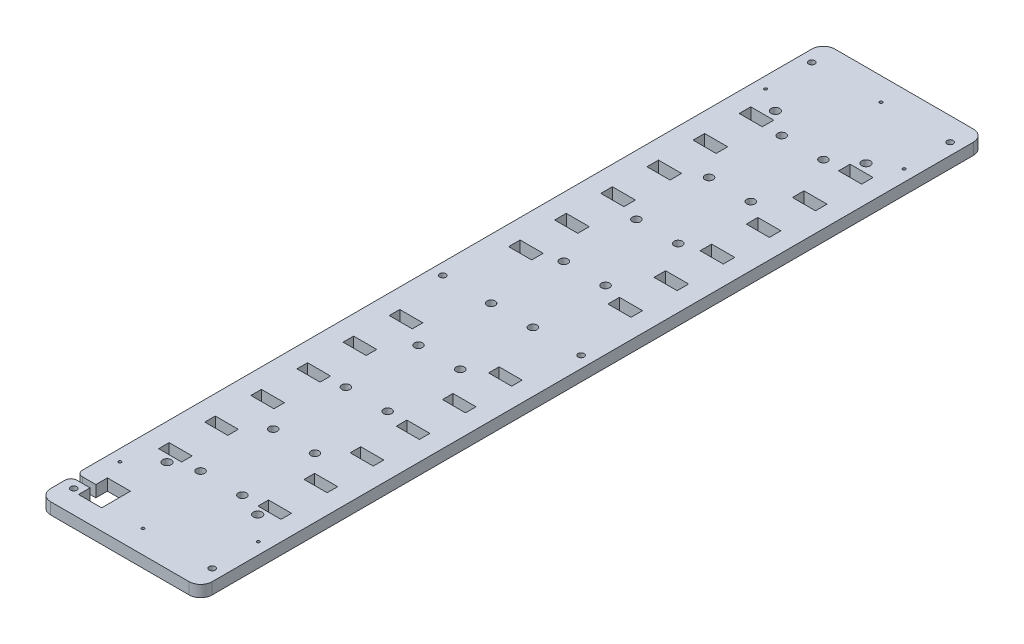
SolidWorks part; units mm, degrees
material "Acrylic (Medium-high impact)"
ref_plane "Front Plane" through (0, 0, 0) normal (0, 0, 1) x (1, 0, 0)
ref_plane "Top Plane" through (0, 0, 0) normal (0, 1, 0) x (1, 0, 0)
ref_plane "Right Plane" through (0, 0, 0) normal (1, 0, 0) x (0, 0, -1)
sketch "Sketch1" plane through (0, 0, 0) normal (0, 1, 0) x (1, 0, 0)
  line L1 (0, 0) -> (-88.9, 0)
  line L2 (0, 0) -> (0, -431.8)
  line L3 (0, -431.8) -> (-88.9, -431.8)
  line L4 (-88.9, 0) -> (-88.9, -431.8)
  dimension "D1" = 88.9
  dimension "D2" = 431.8
extrude "Boss-Extrude1" add sketch "Sketch1" along normal blind 6.35
hole_wizard "M4 Clearance Hole2" positions "Sketch9" profile "Sketch8" hole size "M4" standard "Ansi Metric"
sketch "Sketch9" plane through (0, 6.35, 0) normal (0, 1, 0) x (-1, 0, 0)
  line L2 (0, 215.9) -> (88.9, 215.9) construction
  line L3 (0, 431.8) -> (0, 0) construction
  line L4 (88.9, 0) -> (88.9, 431.8) construction
  line L6 (44.45, 431.8) -> (44.45, 0) construction
  line L7 (88.9, 431.8) -> (0, 431.8) construction
  line L8 (0, 0) -> (88.9, 0) construction
  line L10 (32.95, 215.9) -> (44.45, 215.9) construction
  line L11 (44.45, 215.9) -> (55.95, 215.9) construction
  line L14 (32.95, 375.9) -> (44.45, 375.9) construction
  line L15 (44.45, 375.9) -> (55.95, 375.9) construction
  line L17 (55.95, 55.9) -> (44.45, 55.9) construction
  line L18 (44.45, 55.9) -> (32.95, 55.9) construction
  point P0 (32.95, 215.9)
  point P1 (55.95, 215.9)
  point P76 (32.95, 255.9)
  point P77 (55.95, 255.9)
  point P78 (32.95, 295.9)
  point P79 (55.95, 295.9)
  point P80 (32.95, 335.9)
  point P81 (55.95, 335.9)
  point P82 (32.95, 375.9)
  point P83 (55.95, 375.9)
  point P95 (32.95, 175.9)
  point P96 (55.95, 175.9)
  point P97 (32.95, 135.9)
  point P98 (55.95, 135.9)
  point P99 (32.95, 95.9)
  point P100 (55.95, 95.9)
  point P101 (32.95, 55.9)
  point P102 (55.95, 55.9)
  dimension "D1" = 23
  dimension "D4" = 5
  dimension "D5" = 40
  dimension "D3" = 40
  dimension "D2" = 5
sketch "Sketch8" plane through (-32.95, 6.35, 215.9) normal (1, 0, 0) x (0, 0, 1)
  line L0 (0, 0) -> (0, 14.0519)
  line L1 (0, 14.0519) -> (2.25, 12.7)
  line L2 (2.25, 12.7) -> (2.25, 0)
  line L5 (2.25, 0) -> (0, 0)
  line L10 (0, 14.0519) -> (-2.25, 12.7) construction
  line L11 (0, -6.35) -> (0, 107.95) construction
  dimension "Hole Dia." = 4.5
  dimension "Hole Depth" = 12.7
  dimension "Drill Angle" = 118
hole_wizard "M3 Clearance Hole1" positions "Sketch4" profile "Sketch3" hole size "M3" standard "Ansi Metric"
sketch "Sketch4" plane through (0, 6.35, 0) normal (0, 1, 0) x (-1, 0, 0)
  line L0 (88.9, 12.7) -> (0, 12.7) construction
  line L1 (88.9, 0) -> (88.9, 431.8) construction
  line L2 (0, 431.8) -> (0, 0) construction
  line L4 (0, 0) -> (88.9, 0) construction
  line L5 (82.55, 0) -> (82.55, 431.8) construction
  line L6 (88.9, 431.8) -> (0, 431.8) construction
  line L8 (44.45, 0) -> (44.45, 431.8) construction
  line L10 (88.9, 215.9) -> (0, 215.9) construction
  line L12 (6.35, 12.7) -> (6.35, 431.8) construction
  point P0 (82.55, 12.7)
  point P27 (6.35, 12.7)
  point P28 (6.35, 419.1)
  point P29 (82.55, 419.1)
  point P30 (82.55, 215.9)
  point P32 (6.35, 215.9)
  dimension "D1" = 76.2
  dimension "D2" = 12.7
sketch "Sketch3" plane through (-82.55, 6.35, 12.7) normal (1, 0, 0) x (0, 0, 1)
  line L0 (0, 0) -> (0, 11.0215)
  line L1 (0, 11.0215) -> (1.7, 10)
  line L2 (1.7, 10) -> (1.7, 0)
  line L5 (1.7, 0) -> (0, 0)
  line L10 (0, 11.0215) -> (-1.7, 10) construction
  line L11 (0, -6.35) -> (0, 107.95) construction
  dimension "Hole Dia." = 3.4
  dimension "Hole Depth" = 10
  dimension "Drill Angle" = 118
sketch "Sketch5" plane through (0, 6.35, 0) normal (0, 1, 0) x (1, 0, 0)
  line L0 (-82.55, -12.7) -> (-6.35, -12.7) construction
  line L1 (-82.55, -12.7) -> (-82.55, -38.1) construction
  line L2 (-82.55, -38.1) -> (-6.35, -38.1) construction
  line L3 (-6.35, -38.1) -> (-6.35, -12.7) construction
  line L4 (-82.55, -215.9) -> (-6.35, -215.9) construction
  circle A0 centre (-44.45, -12.7) radius 0.7937
  circle A1 centre (-82.55, -38.1) radius 0.7937
  circle A2 centre (-6.35, -38.1) radius 0.7938
  circle A3 centre (-6.35, -393.7) radius 0.7938
  circle A4 centre (-82.55, -393.7) radius 0.7937
  circle A5 centre (-44.45, -419.1) radius 0.7938
  dimension "D1" = 1.5875
  dimension "D2" = 25.4
extrude "Cut-Extrude2" cut sketch "Sketch5" against normal through all
sketch "Sketch6" plane through (0, 6.35, 0) normal (0, 1, 0) x (-1, 0, 0)
  line L0 (44.45, 55.9) -> (44.45, 53.9) construction
  line L1 (78.15, 50.725) -> (65.45, 50.725)
  line L2 (78.15, 50.725) -> (78.15, 57.075)
  line L3 (78.15, 57.075) -> (65.45, 57.075)
  line L4 (65.45, 50.725) -> (65.45, 57.075)
  line L5 (65.45, 53.9) -> (23.45, 53.9) construction
  line L6 (32.95, 375.9) -> (55.95, 375.9) construction
  line L7 (23.45, 50.725) -> (23.45, 57.075)
  line L8 (10.75, 57.075) -> (23.45, 57.075)
  line L9 (10.75, 50.725) -> (10.75, 57.075)
  line L10 (10.75, 50.725) -> (23.45, 50.725)
  line L11 (78.15, 371) -> (65.45, 371)
  line L12 (78.15, 371) -> (78.15, 376.8)
  line L13 (78.15, 376.8) -> (65.45, 376.8)
  line L14 (65.45, 371) -> (65.45, 376.8)
  line L15 (23.45, 371) -> (23.45, 376.8)
  line L16 (10.75, 376.8) -> (23.45, 376.8)
  line L17 (10.75, 371) -> (10.75, 376.8)
  line L18 (10.75, 371) -> (23.45, 371)
  line L19 (65.45, 373.9) -> (23.45, 373.9) construction
  line L20 (44.45, 373.9) -> (44.45, 375.9) construction
  line L21 (78.15, 345.6) -> (65.45, 345.6)
  line L22 (32.95, 55.9) -> (55.95, 55.9) construction
  line L23 (78.15, 345.6) -> (78.15, 351.4)
  line L24 (78.15, 351.4) -> (65.45, 351.4)
  line L25 (65.45, 345.6) -> (65.45, 351.4)
  line L26 (23.45, 345.6) -> (23.45, 351.4)
  line L27 (10.75, 351.4) -> (23.45, 351.4)
  line L28 (10.75, 345.6) -> (10.75, 351.4)
  line L29 (10.75, 345.6) -> (23.45, 345.6)
  line L30 (78.15, 320.2) -> (65.45, 320.2)
  line L31 (78.15, 320.2) -> (78.15, 326)
  line L32 (78.15, 326) -> (65.45, 326)
  line L33 (65.45, 320.2) -> (65.45, 326)
  line L34 (23.45, 320.2) -> (23.45, 326)
  line L35 (10.75, 326) -> (23.45, 326)
  line L36 (10.75, 320.2) -> (10.75, 326)
  line L37 (10.75, 320.2) -> (23.45, 320.2)
  line L38 (78.15, 294.8) -> (65.45, 294.8)
  line L39 (78.15, 294.8) -> (78.15, 300.6)
  line L40 (78.15, 300.6) -> (65.45, 300.6)
  line L41 (65.45, 294.8) -> (65.45, 300.6)
  line L42 (23.45, 294.8) -> (23.45, 300.6)
  line L43 (10.75, 300.6) -> (23.45, 300.6)
  line L44 (10.75, 294.8) -> (10.75, 300.6)
  line L45 (10.75, 294.8) -> (23.45, 294.8)
  line L46 (78.15, 269.4) -> (65.45, 269.4)
  line L47 (78.15, 269.4) -> (78.15, 275.2)
  line L48 (78.15, 275.2) -> (65.45, 275.2)
  line L49 (65.45, 269.4) -> (65.45, 275.2)
  line L50 (23.45, 269.4) -> (23.45, 275.2)
  line L51 (10.75, 275.2) -> (23.45, 275.2)
  line L52 (10.75, 269.4) -> (10.75, 275.2)
  line L53 (10.75, 269.4) -> (23.45, 269.4)
  line L54 (78.15, 244) -> (65.45, 244)
  line L55 (78.15, 244) -> (78.15, 249.8)
  line L56 (78.15, 249.8) -> (65.45, 249.8)
  line L57 (65.45, 244) -> (65.45, 249.8)
  line L58 (23.45, 244) -> (23.45, 249.8)
  line L59 (10.75, 249.8) -> (23.45, 249.8)
  line L60 (10.75, 244) -> (10.75, 249.8)
  line L61 (10.75, 244) -> (23.45, 244)
  line L62 (78.15, 76.125) -> (65.45, 76.125)
  line L63 (78.15, 76.125) -> (78.15, 82.475)
  line L64 (78.15, 82.475) -> (65.45, 82.475)
  line L65 (65.45, 76.125) -> (65.45, 82.475)
  line L66 (23.45, 76.125) -> (23.45, 82.475)
  line L67 (10.75, 82.475) -> (23.45, 82.475)
  line L68 (10.75, 76.125) -> (10.75, 82.475)
  line L69 (10.75, 76.125) -> (23.45, 76.125)
  line L70 (78.15, 101.525) -> (65.45, 101.525)
  line L71 (78.15, 101.525) -> (78.15, 107.875)
  line L72 (78.15, 107.875) -> (65.45, 107.875)
  line L73 (65.45, 101.525) -> (65.45, 107.875)
  line L74 (23.45, 101.525) -> (23.45, 107.875)
  line L75 (10.75, 107.875) -> (23.45, 107.875)
  line L76 (10.75, 101.525) -> (10.75, 107.875)
  line L77 (10.75, 101.525) -> (23.45, 101.525)
  line L78 (78.15, 126.925) -> (65.45, 126.925)
  line L79 (78.15, 126.925) -> (78.15, 133.275)
  line L80 (78.15, 133.275) -> (65.45, 133.275)
  line L81 (65.45, 126.925) -> (65.45, 133.275)
  line L82 (23.45, 126.925) -> (23.45, 133.275)
  line L83 (10.75, 133.275) -> (23.45, 133.275)
  line L84 (10.75, 126.925) -> (10.75, 133.275)
  line L85 (10.75, 126.925) -> (23.45, 126.925)
  line L86 (78.15, 152.325) -> (65.45, 152.325)
  line L87 (78.15, 152.325) -> (78.15, 158.675)
  line L88 (78.15, 158.675) -> (65.45, 158.675)
  line L89 (65.45, 152.325) -> (65.45, 158.675)
  line L90 (23.45, 152.325) -> (23.45, 158.675)
  line L91 (10.75, 158.675) -> (23.45, 158.675)
  line L92 (10.75, 152.325) -> (10.75, 158.675)
  line L93 (10.75, 152.325) -> (23.45, 152.325)
  line L94 (78.15, 177.725) -> (65.45, 177.725)
  line L95 (78.15, 177.725) -> (78.15, 184.075)
  line L96 (78.15, 184.075) -> (65.45, 184.075)
  line L97 (65.45, 177.725) -> (65.45, 184.075)
  line L98 (23.45, 177.725) -> (23.45, 184.075)
  line L99 (10.75, 184.075) -> (23.45, 184.075)
  line L100 (10.75, 177.725) -> (10.75, 184.075)
  line L101 (10.75, 177.725) -> (23.45, 177.725)
  circle A0 centre (32.95, 55.9) radius 2.25 construction
  circle A1 centre (55.95, 55.9) radius 2.25 construction
  circle A2 centre (55.95, 375.9) radius 2.25 construction
  circle A6 centre (32.95, 375.9) radius 2.25 construction
  dimension "D1" = 6.35
  dimension "D2" = 42
  dimension "D3" = 42
  dimension "D4" = 12.7
  dimension "D6" = 2
  dimension "D7" = 12.7
  dimension "D5" = 5.8
  dimension "D8" = 2
  dimension "D10" = 25.4
  dimension "D12" = 25.4
  dimension "D9" = 6
  dimension "D11" = 6
extrude "Cut-Extrude3" cut sketch "Sketch6" against normal through all
fillet "Fillet1" radius 6.35 4 edges at (-88.9, 3.175, 0) (0, 3.175, 0) (0, 3.175, 431.8) (-88.9, 3.175, 431.8)
sketch "Sketch10" plane through (0, 6.35, 0) normal (0, 1, 0) x (1, 0, 0)
  line L0 (-44.45, 0) -> (-44.45, -431.8) construction
  line L1 (-6.35, 0) -> (-82.55, 0) construction
  line L2 (-82.55, -431.8) -> (-6.35, -431.8) construction
  line L3 (-44.45, -380.9) -> (-23.45, -380.9) construction
  line L4 (-23.45, -380.9) -> (-23.45, -45.9) construction
  line L5 (-23.45, -45.9) -> (-44.45, -45.9) construction
  line L6 (-19.4812, -45.9) -> (-19.4812, -380.9) construction
  circle A0 centre (-32.95, -55.9) radius 2.25 construction
  circle A1 centre (-32.95, -375.9) radius 2.25 construction
  circle A2 centre (-19.4812, -380.9) radius 3.9688 construction
  circle A3 centre (-19.4812, -45.9) radius 3.9688 construction
  circle A4 centre (-69.4187, -45.9) radius 3.9688 construction
  circle A5 centre (-69.4187, -380.9) radius 3.9687 construction
  circle A6 centre (-19.4812, -380.9) radius 2.3813
  circle A7 centre (-69.4187, -380.9) radius 2.3813
  circle A8 centre (-69.4187, -45.9) radius 2.3813
  circle A9 centre (-19.4812, -45.9) radius 2.3813
  dimension "D4" = 7.9375
  dimension "D5" = 4.7625
  dimension "D1" = 21
  dimension "D2" = 10
  dimension "D3" = 5
extrude "Cut-Extrude4" cut sketch "Sketch10" against normal through all
sketch "Sketch11" plane through (0, 6.35, 0) normal (0, 1, 0) x (1, 0, 0)
  line L0 (-88.9, -411.1625) -> (-78.3488, -411.1625)
  line L1 (-88.9, -6.35) -> (-88.9, -425.45) construction
  line L2 (-78.3488, -411.1625) -> (-78.3488, -404.8125)
  line L3 (-78.3488, -404.8125) -> (-65.6488, -404.8125)
  line L4 (-65.6488, -404.8125) -> (-65.6488, -420.6875)
  line L5 (-65.6488, -420.6875) -> (-78.3488, -420.6875)
  line L6 (-78.3488, -420.6875) -> (-78.3488, -414.3375)
  line L7 (-78.3488, -414.3375) -> (-88.9, -414.3375)
  line L8 (-88.9, -414.3375) -> (-88.9, -411.1625)
  line L9 (-88.9, -412.75) -> (-65.6488, -412.75) construction
  line L10 (-82.55, -431.8) -> (-6.35, -431.8) construction
  dimension "D1" = 3.175
  dimension "D2" = 19.05
  dimension "D3" = 10.5512
  dimension "D4" = 12.7
  dimension "D5" = 15.875
extrude "Cut-Extrude5" cut sketch "Sketch11" against normal through all
fillet "Fillet2" radius 3.175 2 edges at (-88.9, 3.175, 411.1625) (-88.9, 3.175, 414.3375)
